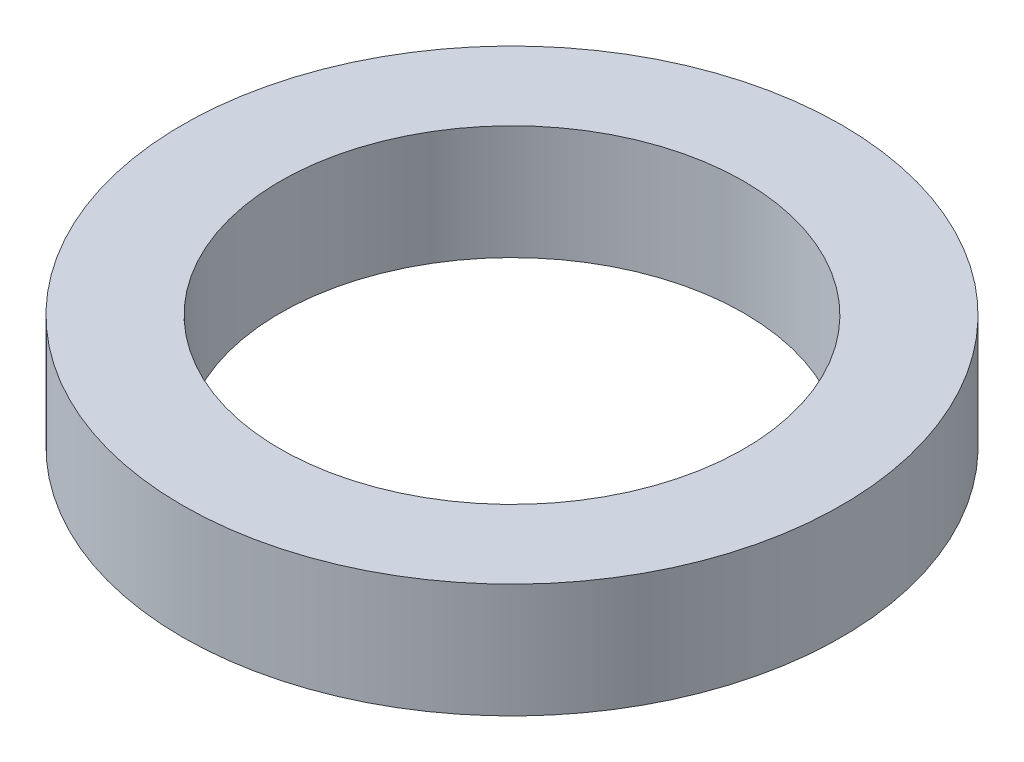
SolidWorks part; units mm, degrees
ref_plane "Front Plane" through (0, 0, 0) normal (0, 0, 1) x (1, 0, 0)
ref_plane "Top Plane" through (0, 0, 0) normal (0, 1, 0) x (1, 0, 0)
ref_plane "Right Plane" through (0, 0, 0) normal (1, 0, 0) x (0, 0, -1)
sketch "Sketch1" plane through (0, 0, 0) normal (0, 0, 1) x (1, 0, 0)
  line L0 (0, -200) -> (0, 100) construction
  line L1 (3.25, 2.5) -> (3.25, 4.1)
  line L2 (3.25, 4.1) -> (4.619, 4.1)
  line L3 (4.619, 4.1) -> (4.619, 2.5)
  line L4 (4.619, 2.5) -> (3.25, 2.5)
revolve "Revolve1" add sketch "Sketch1" angle 360 about L0
